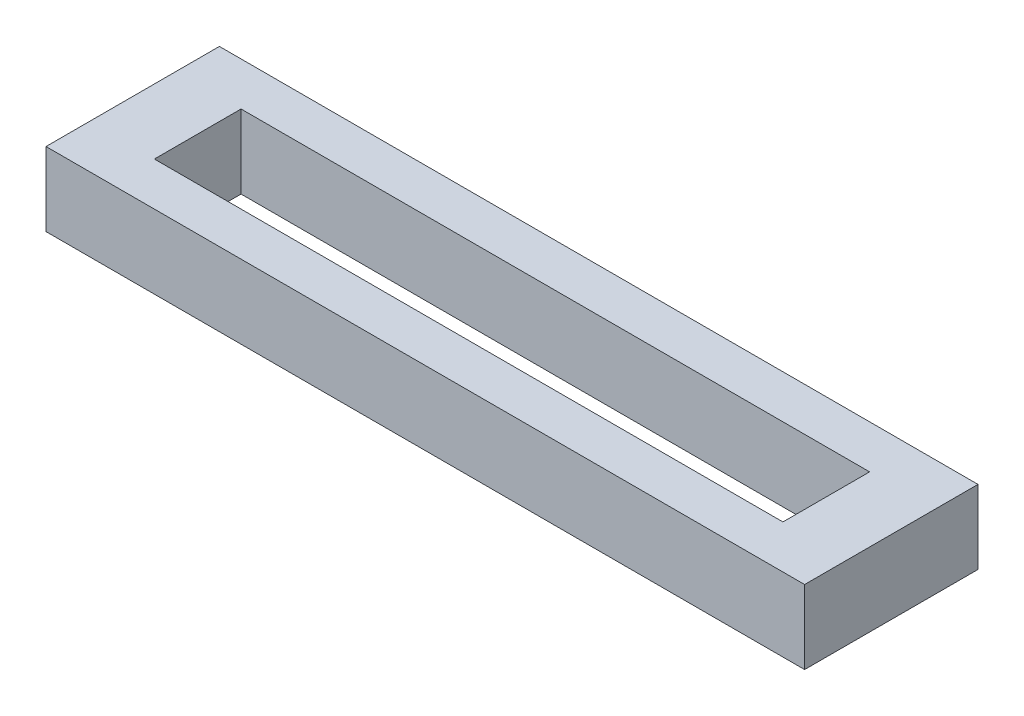
SolidWorks part; units mm, degrees
ref_plane "前视基准面" through (0, 0, 0) normal (0, 0, 1) x (1, 0, 0)
ref_plane "上视基准面" through (0, 0, 0) normal (0, 1, 0) x (1, 0, 0)
ref_plane "右视基准面" through (0, 0, 0) normal (1, 0, 0) x (0, 0, -1)
other "Configuration Table"
sketch "草图1" plane through (0, 0, 0) normal (0, 1, 0) x (1, 0, 0)
  line L1 (-17.5, 4) -> (17.5, 4)
  line L2 (-17.5, 4) -> (-17.5, -4)
  line L3 (-17.5, -4) -> (17.5, -4)
  line L4 (17.5, 4) -> (17.5, -4)
  line L5 (-17.5, 4) -> (17.5, -4) construction
  line L6 (-17.5, -4) -> (17.5, 4) construction
  line L7 (-14.5, 2) -> (14.5, 2)
  line L8 (-14.5, 2) -> (-14.5, -2)
  line L9 (-14.5, -2) -> (14.5, -2)
  line L10 (14.5, 2) -> (14.5, -2)
  line L11 (-14.5, 2) -> (14.5, -2) construction
  line L12 (-14.5, -2) -> (14.5, 2) construction
  point P0 (0, 0)
  point P6 (0, 0)
  dimension "D1" = 35
  dimension "D2" = 8
  dimension "D3" = 2
  dimension "D4" = 3
extrude "凸台-拉伸1" add sketch "草图1" along normal blind 3.4
